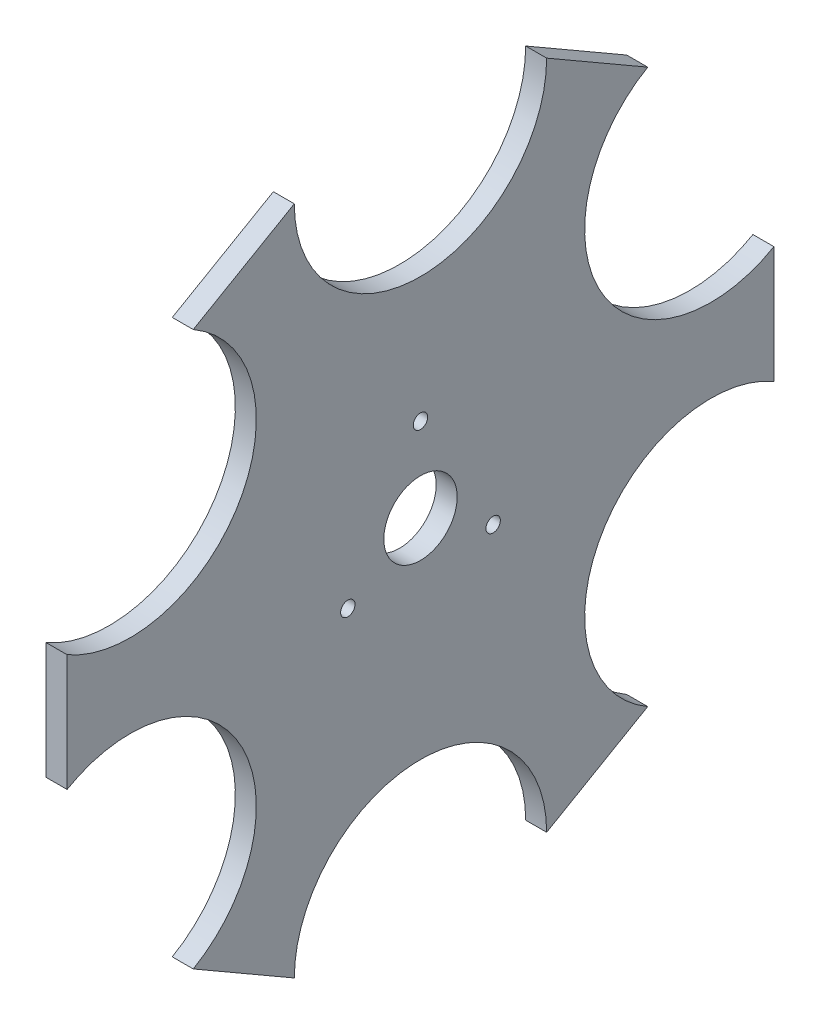
SolidWorks part; units mm, degrees
ref_plane "Front Plane" through (0, 0, 0) normal (0, 0, 1) x (1, 0, 0)
ref_plane "Top Plane" through (0, 0, 0) normal (0, 1, 0) x (1, 0, 0)
ref_plane "Right Plane" through (0, 0, 0) normal (1, 0, 0) x (0, 0, -1)
sketch "Sketch1" plane through (0, 0, 0) normal (1, 0, 0) x (0, 0, -1)
  line L0 (0, 0) -> (0, 101.5) construction
  line L1 (38.2, 101.5) -> (-38.2, 101.5) construction
  line L2 (107.0016, 17.6678) -> (68.8016, 83.8322) construction
  line L3 (0, 0) -> (87.9016, 50.75) construction
  line L4 (68.8016, -83.8322) -> (107.0016, -17.6678) construction
  line L5 (0, 0) -> (87.9016, -50.75) construction
  line L6 (-38.2, -101.5) -> (38.2, -101.5) construction
  line L7 (0, 0) -> (0, -101.5) construction
  line L8 (-107.0016, -17.6678) -> (-68.8016, -83.8322) construction
  line L9 (0, 0) -> (-87.9016, -50.75) construction
  line L10 (-68.8016, 83.8322) -> (-107.0016, 17.6678) construction
  line L11 (0, 0) -> (-87.9016, 50.75) construction
  line L12 (38.2, 101.5) -> (68.8016, 83.8322)
  line L13 (107.0016, 17.6678) -> (107.0016, -17.6678)
  line L14 (68.8016, -83.8322) -> (38.2, -101.5)
  line L15 (-38.2, -101.5) -> (-68.8016, -83.8322)
  line L16 (-107.0016, -17.6678) -> (-107.0016, 17.6678)
  line L17 (-68.8016, 83.8322) -> (-38.2, 101.5)
  arc A0 (-38.2, 101.5) -> (38.2, 101.5) centre (0, 101.5) ccw
  arc A1 (68.8016, 83.8322) -> (107.0016, 17.6678) centre (87.9016, 50.75) ccw
  arc A2 (107.0016, -17.6678) -> (68.8016, -83.8322) centre (87.9016, -50.75) ccw
  arc A3 (38.2, -101.5) -> (-38.2, -101.5) centre (0, -101.5) ccw
  arc A4 (-68.8016, -83.8322) -> (-107.0016, -17.6678) centre (-87.9016, -50.75) ccw
  arc A5 (-107.0016, 17.6678) -> (-68.8016, 83.8322) centre (-87.9016, 50.75) ccw
  circle A6 centre (0, 0) radius 11.1106
  point P6 (0, 101.5)
  point P24 (0, 0)
  point P35 (0, 0)
  point P52 (0, 0)
  dimension "D6" = 22.2212
  dimension "D1" = 76.4
  dimension "D2" = 101.5
  dimension "D3" = 6
  dimension "D4" = 6
  dimension "D5" = 6
extrude "Boss-Extrude1" add sketch "Sketch1" along normal blind 6.35
hole_wizard "11/64 (0.17188) Diameter Hole1" positions "Sketch5" profile "Sketch4" hole size "11/64" standard "ANSI Inch" end condition through all
sketch "Sketch5" plane through (6.35, 0, 0) normal (1, 0, 0) x (0, 0, -1)
  point P0 (0, 25.4)
  dimension "D1" = 25.4
sketch "Sketch4" plane through (6.35, 25.4, 0) normal (0, 1, 0) x (0, 0, -1)
  line L0 (0, 0) -> (0, 6.35)
  line L1 (0, 6.35) -> (2.1829, 6.35)
  line L2 (2.1829, 6.35) -> (2.1829, 0)
  line L5 (2.1829, 0) -> (0, 0)
  line L11 (0, -6.35) -> (0, 107.95) construction
  dimension "Thru Hole Dia." = 4.3658
  dimension "Thru Hole Depth" = 6.35
pattern_circular "CirPattern1" count 3 every 120 about axis through (0, 0, 0) along (1, 0, 0) of "11/64 (0.17188) Diameter Hole1"
